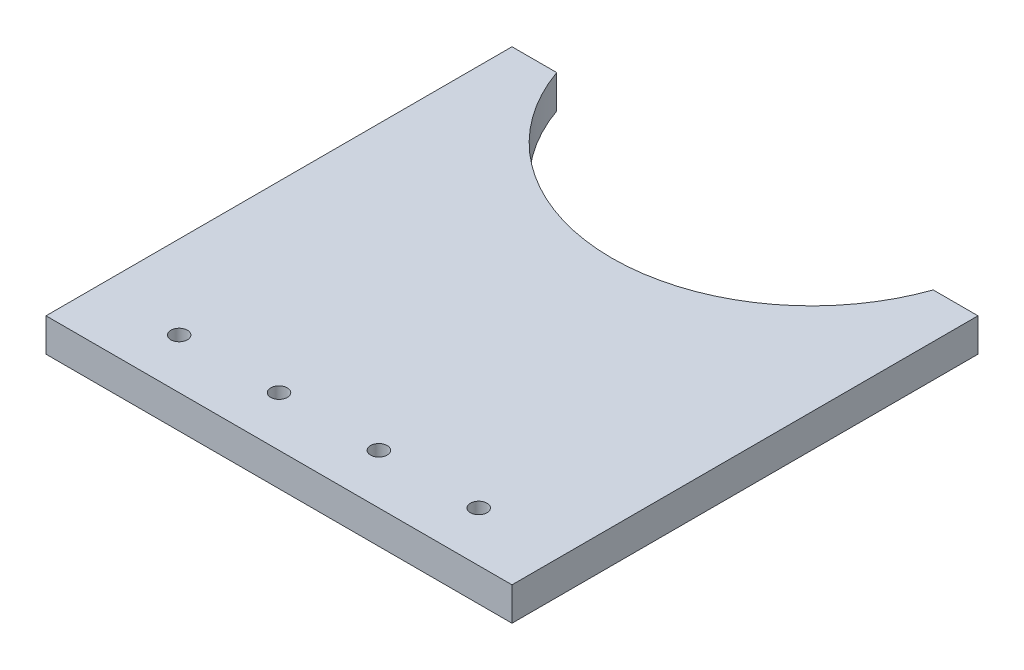
SolidWorks part; units mm, degrees
ref_plane "Front Plane" through (0, 0, 0) normal (0, 0, 1) x (1, 0, 0)
ref_plane "Top Plane" through (0, 0, 0) normal (0, 1, 0) x (1, 0, 0)
ref_plane "Right Plane" through (0, 0, 0) normal (1, 0, 0) x (0, 0, -1)
sketch "Sketch1" plane through (0, 0, 0) normal (0, 1, 0) x (1, 0, 0)
  line L0 (0, 0) -> (0, -203.2) construction
  line L1 (-88.9, -25.4) -> (-71.842, -25.4)
  line L2 (-88.9, -25.4) -> (-88.9, -203.2)
  line L3 (-88.9, -203.2) -> (88.9, -203.2)
  line L4 (88.9, -25.4) -> (88.9, -203.2)
  line L5 (71.842, -25.4) -> (88.9, -25.4)
  arc A0 (-71.842, -25.4) -> (71.842, -25.4) centre (0, 0) ccw
  dimension "D1" = 152.4
  dimension "D2" = 177.8
  dimension "D3" = 25.4
  dimension "D4" = 177.8
extrude "Boss-Extrude1" add sketch "Sketch1" along normal blind 12.7
sketch "Sketch2" plane through (0, 12.7, 0) normal (0, 1, 0) x (1, 0, 0)
  line L0 (-88.9, -184.15) -> (88.9, -184.15) construction
  line L1 (-88.9, -25.4) -> (-88.9, -203.2) construction
  line L2 (88.9, -203.2) -> (88.9, -25.4) construction
  line L3 (0, -184.15) -> (0, -105.9962) construction
  line L4 (-88.9, -203.2) -> (88.9, -203.2) construction
  circle A0 centre (-19.05, -184.15) radius 3.175
  circle A1 centre (19.05, -184.15) radius 3.175
  circle A2 centre (57.15, -184.15) radius 3.175
  circle A3 centre (-57.15, -184.15) radius 3.175
  dimension "D2" = 6.35
  dimension "D1" = 19.05
  dimension "D3" = 38.1
  dimension "D4" = 38.1
  dimension "D5" = 38.1
  dimension "D6" = 19.05
extrude "Cut-Extrude1" cut sketch "Sketch2" against normal through all
